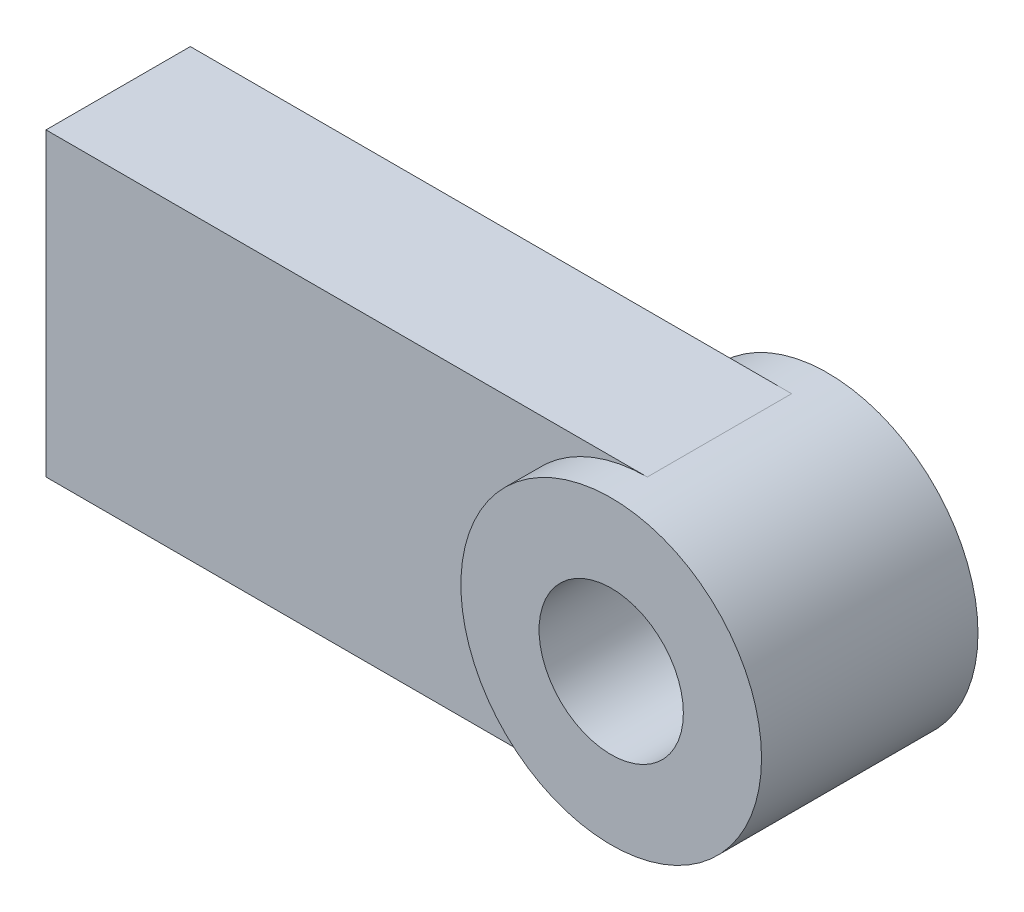
SolidWorks part; units mm, degrees
ref_plane "Front Plane" through (0, 0, 0) normal (0, 0, 1) x (1, 0, 0)
ref_plane "Top Plane" through (0, 0, 0) normal (0, 1, 0) x (1, 0, 0)
ref_plane "Right Plane" through (0, 0, 0) normal (1, 0, 0) x (0, 0, -1)
sketch "Sketch1" plane through (0, 0, 0) normal (0, 0, 1) x (1, 0, 0)
  line L0 (0, 0) -> (50000, 0)
  line L1 (50000, 0) -> (50000, 25000)
  line L2 (50000, 25000) -> (0, 25000)
  line L3 (0, 25000) -> (0, 0)
  dimension "D1" = 25000
  dimension "D2" = 50000
extrude "Boss-Extrude1" add sketch "Sketch1" against normal blind 12000
sketch "Sketch2" plane through (0, 0, 0) normal (0, 0, 1) x (1, 0, 0)
  line L0 (50000, 0) -> (50000, 25000) construction
  circle A0 centre (50000, 12500) radius 12500
  dimension "D1" = 25000
extrude "Boss-Extrude2" add sketch "Sketch2" against normal blind 15000
sketch "Sketch3" plane through (0, 0, 0) normal (0, 0, 1) x (1, 0, 0)
  circle A0 centre (50000, 12500) radius 12500
  dimension "D1" = 25000
extrude "Boss-Extrude3" add sketch "Sketch3" along normal blind 3000
sketch "Sketch4" plane through (0, 0, 3000) normal (0, 0, 1) x (1, 0, 0)
  circle A0 centre (50000, 12500) radius 6000
  dimension "D1" = 12000
extrude "Cut-Extrude1" cut sketch "Sketch4" against normal blind 18000
